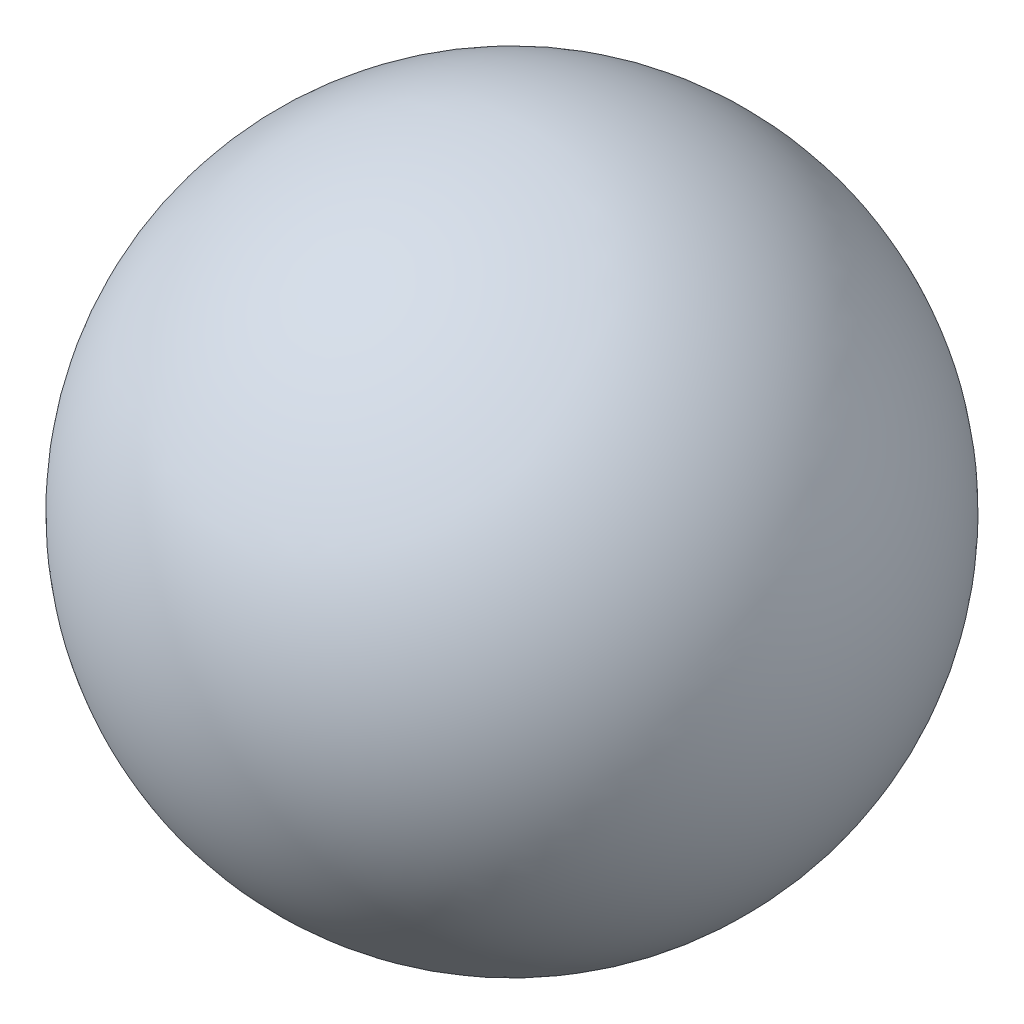
SolidWorks part; units mm, degrees
material "Air"
ref_plane "Front Plane" through (0, 0, 0) normal (0, 0, 1) x (1, 0, 0)
ref_plane "Top Plane" through (0, 0, 0) normal (0, 1, 0) x (1, 0, 0)
ref_plane "Right Plane" through (0, 0, 0) normal (1, 0, 0) x (0, 0, -1)
sketch "Sketch1" plane through (0, 0, 0) normal (0, 1, 0) x (1, 0, 0)
  line L0 (0, 350) -> (0, -350)
  arc A0 (0, -350) -> (0, 350) centre (0, 0) ccw
  dimension "D1" = 350
revolve "Revolve1" add sketch "Sketch1" angle 360 about L0
